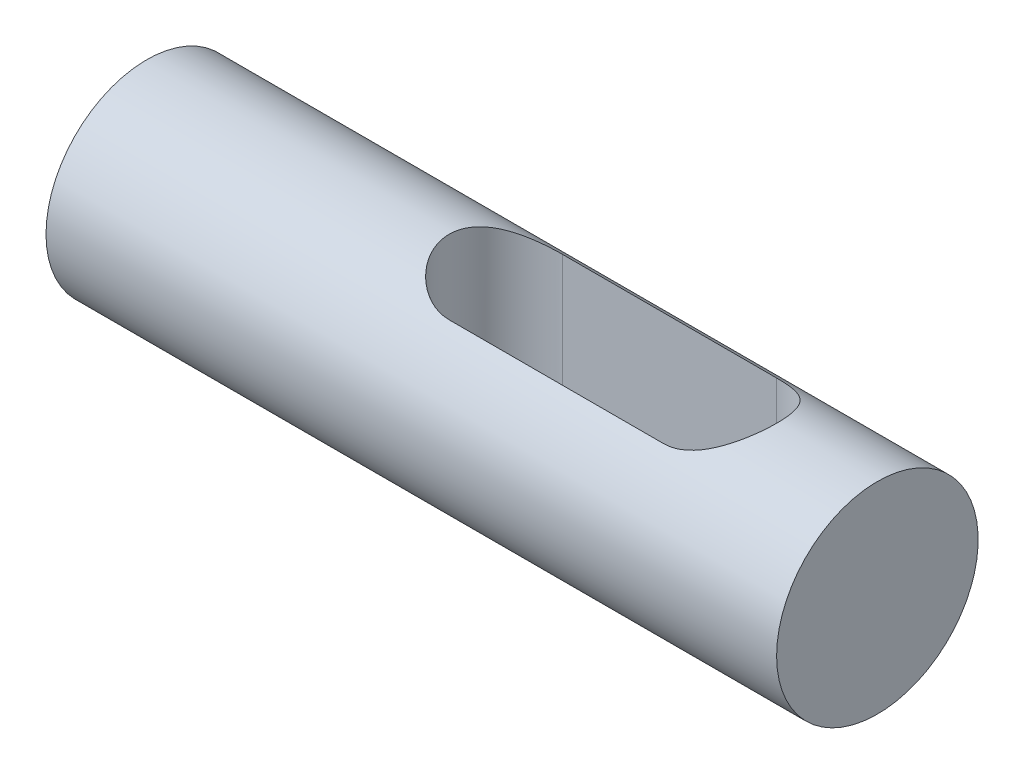
SolidWorks part; units mm, degrees
ref_plane "Front Plane" through (0, 0, 0) normal (0, 0, 1) x (1, 0, 0)
ref_plane "Top Plane" through (0, 0, 0) normal (0, 1, 0) x (1, 0, 0)
ref_plane "Right Plane" through (0, 0, 0) normal (1, 0, 0) x (0, 0, -1)
sketch "Sketch1" plane through (0, 0, 0) normal (0, 1, 0) x (1, 0, 0)
  line L1 (-7.25, 2) -> (7.25, 2)
  line L2 (-7.25, 2) -> (-7.25, 0)
  line L3 (-7.25, 0) -> (7.25, 0)
  line L4 (7.25, 2) -> (7.25, 0)
  line L5 (-7.25, 2) -> (7.25, 0) construction
  line L6 (-7.25, 0) -> (7.25, 2) construction
  point P4 (0, 1)
  dimension "D1" = 14.5
  dimension "D2" = 2
revolve "Revolve1" add sketch "Sketch1" angle 360 about L3
sketch "Sketch2" plane through (0, 0, 0) normal (0, 1, 0) x (1, 0, 0)
  line L0 (-2.25, 2) -> (-2.25, -2) construction
  line L1 (-7.25, 2) -> (-7.25, -2) construction
  line L3 (-0.125, 1.125) -> (4.125, 1.125)
  line L5 (-0.125, -1.125) -> (4.125, -1.125)
  arc A0 (-0.125, 1.125) -> (-0.125, -1.125) centre (-0.125, 0) ccw
  arc A1 (4.125, -1.125) -> (4.125, 1.125) centre (4.125, 0) ccw
  point P2 (-2.25, 0)
  point P7 (2.6198, -0.467)
  dimension "D3" = 4.25
  dimension "D4" = 1.125
  dimension "D1" = 4
  dimension "D2" = 5
  dimension "D5" = 2.125
extrude "Cut-Extrude1" cut sketch "Sketch2" against normal through all both and the other way through all
